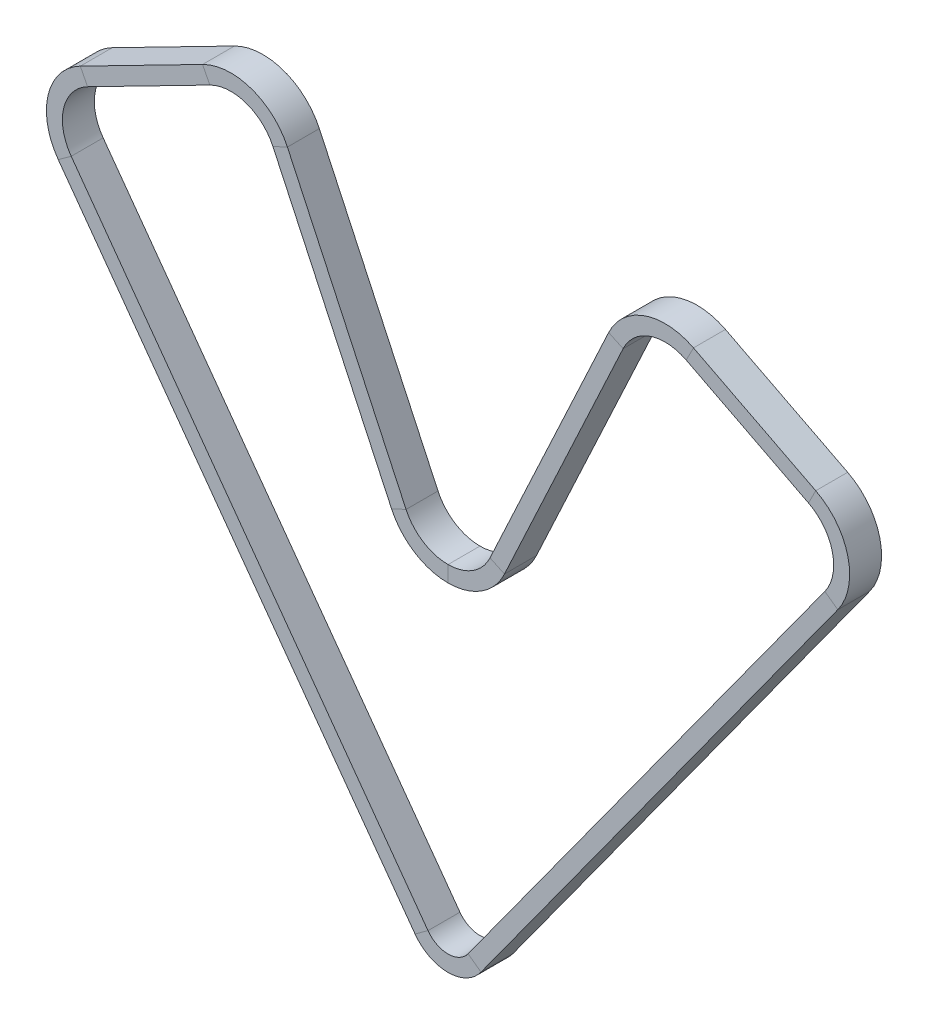
SolidWorks part; units mm, degrees
ref_plane "Alzado" through (0, 0, 0) normal (0, 0, 1) x (1, 0, 0)
ref_plane "Planta" through (0, 0, 0) normal (0, 1, 0) x (1, 0, 0)
ref_plane "Vista lateral" through (0, 0, 0) normal (1, 0, 0) x (0, 0, -1)
sketch "Croquis2" plane through (0, 0, 0) normal (0, 0, 1) x (1, 0, 0)
  line L0 (-135.9209, 130.6191) -> (135.9209, 130.6191) construction
  line L1 (-212.4704, 91.4252) -> (212.4704, 91.4252) construction
  line L2 (0, 0) -> (0, 91.4252) construction
  line L3 (0, 91.4252) -> (0, 130.6191) construction
  line L4 (-149.1374, 156.4324) -> (-225.687, 117.2384)
  line L5 (-235.9508, 74.4054) -> (-12.5498, -233.7958)
  line L6 (12.5498, -233.7958) -> (235.9508, 74.4054)
  line L7 (225.687, 117.2384) -> (149.1374, 156.4324)
  line L8 (109.6368, 142.8727) -> (35.3475, -16.4789)
  line L9 (-35.3475, -16.4789) -> (-109.6368, 142.8727)
  arc A0 (-225.687, 117.2384) -> (-235.9508, 74.4054) centre (-212.4704, 91.4252) ccw
  arc A1 (235.9508, 74.4054) -> (225.687, 117.2384) centre (212.4704, 91.4252) ccw
  arc A2 (-109.6368, 142.8727) -> (-149.1374, 156.4324) centre (-135.9209, 130.6191) ccw
  arc A3 (149.1374, 156.4324) -> (109.6368, 142.8727) centre (135.9209, 130.6191) ccw
  arc A4 (-35.3475, -16.4789) -> (35.3475, -16.4789) centre (0, 0) ccw
  arc A5 (-12.5498, -233.7958) -> (12.5498, -233.7958) centre (0, -224.699) ccw
  dimension "D2" = 58
  dimension "D5" = 78
  dimension "D8" = 31
  dimension "D1" = 424.9409
  dimension "D3" = 271.8417
  dimension "D4" = 86
  dimension "D6" = 188.5095
  dimension "D7" = 224.699
sketch "Croquis3" plane through (0, 0, 0) normal (1, 0, 0) x (0, 0, -1)
  line L1 (0, -16.4789) -> (0, -39) construction
  line L2 (0, -16.4789) -> (0, -39) construction
  line L3 (10, -39) -> (-10, -39)
  line L4 (10, -29) -> (-10, -29)
  line L5 (-10, -29) -> (-10, -39)
  line L6 (10, -29) -> (10, -39)
  point P5 (0, -39)
  point P8 (0, -29)
  dimension "D1" = 20
  dimension "D2" = 10
sweep "Barrer1" add profiles "Croquis3" path "Croquis2"
